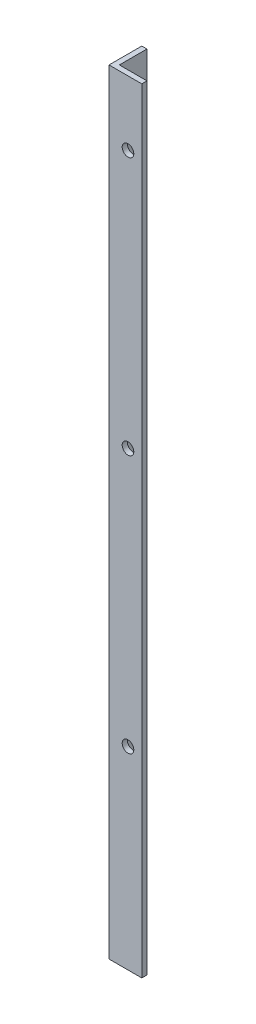
SolidWorks part; units mm, degrees
material "Alumina"
ref_plane "Front Plane" through (0, 0, 0) normal (0, 0, 1) x (1, 0, 0)
ref_plane "Top Plane" through (0, 0, 0) normal (0, 1, 0) x (1, 0, 0)
ref_plane "Right Plane" through (0, 0, 0) normal (1, 0, 0) x (0, 0, -1)
sketch "Sketch1" plane through (0, 0, 0) normal (0, 1, 0) x (1, 0, 0)
  line L0 (0, 0) -> (12.7, 0)
  line L1 (0, 0) -> (0, 12.7)
  line L2 (2, 2) -> (12.7, 2)
  line L3 (2, 2) -> (2, 12.7)
  line L4 (0, 12.7) -> (2, 12.7)
  line L5 (12.7, 0) -> (12.7, 2)
  dimension "D1" = 12.7
  dimension "D3" = 12.7
  dimension "D2" = 2
extrude "Boss-Extrude1" add sketch "Sketch1" along normal blind 300
sketch "Sketch2" plane through (0, 0, -2) normal (0, 0, -1) x (-1, 0, 0)
  line L0 (-7.35, 300) -> (-7.35, 0) construction
  line L3 (-12.7, 300) -> (-2, 300) construction
  line L4 (-12.7, 0) -> (-2, 0) construction
  circle A2 centre (-7.35, 275) radius 2.25
  circle A5 centre (-7.35, 175) radius 2.25
  circle A6 centre (-7.35, 75) radius 2.25
  dimension "D1" = 4.5
  dimension "D2" = 25
extrude "Cut-Extrude1" cut sketch "Sketch2" against normal blind 10
sketch "Sketch3" plane through (2, 0, 0) normal (1, 0, 0) x (0, 0, -1)
  line L0 (7.35, 300) -> (7.35, 0) construction
  line L1 (2, 300) -> (12.7, 300) construction
  line L2 (2, 0) -> (12.7, 0) construction
  circle A0 centre (7.35, 225) radius 2.25
  circle A2 centre (7.35, 125) radius 2.25
  circle A3 centre (7.35, 25) radius 2.25
  dimension "D1" = 4.5
  dimension "D2" = 75
extrude "Cut-Extrude2" cut sketch "Sketch3" against normal blind 10
sketch "Sketch4" plane through (0, 0, 0) normal (-1, 0, 0) x (0, 0, 1)
  circle A0 centre (-7.94, 253.6) radius 1.85
sketch "Sketch5" plane through (0, 0, 0) normal (-1, 0, 0) x (0, 0, 1)
  circle A0 centre (-7.94, 253.6) radius 2.25
extrude "Cut-Extrude3" cut sketch "Sketch5" against normal blind 10
